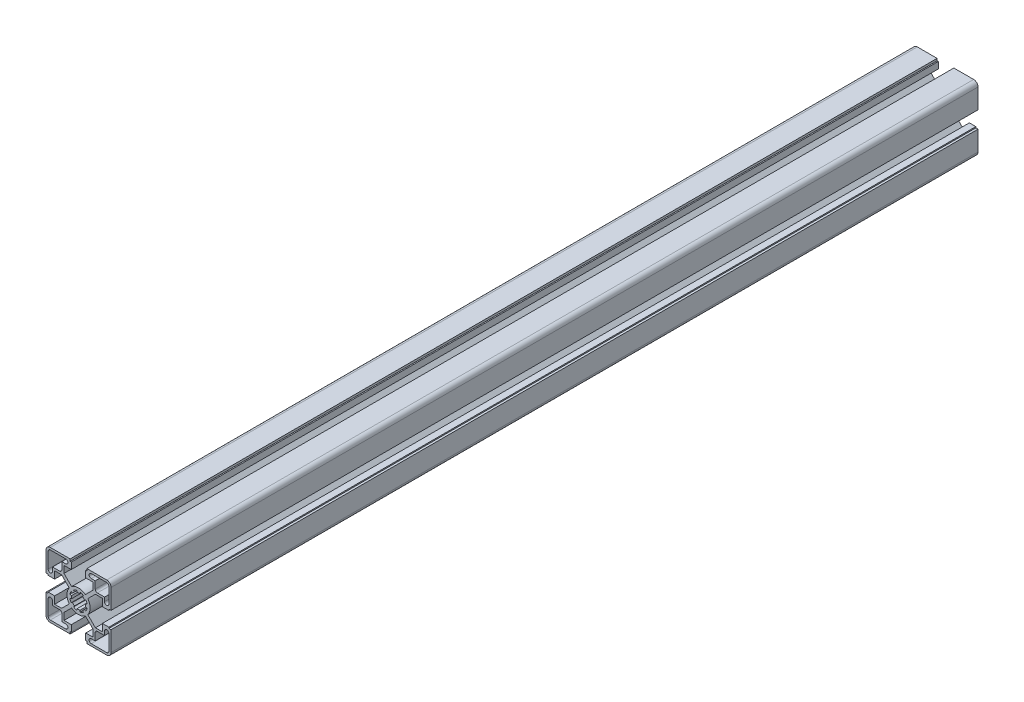
SolidWorks part; units mm, degrees
ref_plane "Front Plane" through (0, 0, 0) normal (0, 0, 1) x (1, 0, 0)
ref_plane "Top Plane" through (0, 0, 0) normal (0, 1, 0) x (1, 0, 0)
ref_plane "Right Plane" through (0, 0, 0) normal (1, 0, 0) x (0, 0, -1)
sketch "Sketch1" plane through (0, 0, 0) normal (0, 0, 1) x (1, 0, 0)
  line L2 (-19.5072, 22.5044) -> (-5.7912, 22.5044)
  line L3 (-5.7912, 22.5044) -> (-5.7912, 21.0058)
  line L4 (-5.7912, 21.0058) -> (-5.0038, 21.0058)
  line L6 (-5.0038, 21.0058) -> (-5.0038, 16.51)
  line L7 (-5.0038, 16.51) -> (-10.0457, 16.51)
  line L8 (-10.0457, 16.51) -> (-10.0457, 11.6801)
  line L9 (-10.0457, 11.6801) -> (-4.781, 6.4154)
  line L11 (-11.6801, 10.0457) -> (-6.4154, 4.781)
  line L12 (-16.51, 10.0457) -> (-11.6801, 10.0457)
  line L13 (-16.51, 5.0038) -> (-16.51, 10.0457)
  line L14 (-21.0058, 5.0038) -> (-16.51, 5.0038)
  line L15 (-21.0058, 5.7912) -> (-21.0058, 5.0038)
  line L16 (-22.5044, 5.7912) -> (-21.0058, 5.7912)
  line L17 (-22.5044, 19.5072) -> (-22.5044, 5.7912)
  line L18 (-18.0086, 11.5443) -> (-13.0429, 11.5443)
  line L19 (-18.0086, 11.5443) -> (-18.0086, 8.7884)
  line L20 (-11.5443, 18.0086) -> (-11.5443, 13.0429)
  line L21 (-21.0058, 19.5072) -> (-21.0058, 8.7884)
  line L23 (-11.5443, 18.0086) -> (-8.7884, 18.0086)
  line L24 (-19.5072, 21.0058) -> (-8.7884, 21.0058)
  line L25 (1.1893, 5.9789) -> (0.9762, 4.9077)
  line L26 (-1.1893, 5.9789) -> (-0.9762, 4.9077)
  line L27 (5.0686, 3.3868) -> (4.1605, 2.78)
  line L28 (3.3868, 5.0686) -> (2.78, 4.1605)
  line L29 (5.9789, -1.1893) -> (4.9077, -0.9762)
  line L30 (5.9789, 1.1893) -> (4.9077, 0.9762)
  line L31 (3.3868, -5.0686) -> (2.78, -4.1605)
  line L32 (5.0686, -3.3868) -> (4.1605, -2.78)
  line L33 (-1.1893, -5.9789) -> (-0.9762, -4.9077)
  line L34 (1.1893, -5.9789) -> (0.9762, -4.9077)
  line L35 (-5.0686, -3.3868) -> (-4.1605, -2.78)
  line L36 (-3.3868, -5.0686) -> (-2.78, -4.1605)
  line L37 (-5.9789, 1.1893) -> (-4.9077, 0.9762)
  line L38 (-5.9789, -1.1893) -> (-4.9077, -0.9762)
  line L39 (-3.3868, 5.0686) -> (-2.78, 4.1605)
  line L40 (-5.0686, 3.3868) -> (-4.1605, 2.78)
  line L41 (11.5443, 18.0086) -> (8.7884, 18.0086)
  line L42 (19.5072, 21.0058) -> (8.7884, 21.0058)
  line L43 (19.5072, 22.5044) -> (5.7912, 22.5044)
  line L44 (5.7912, 22.5044) -> (5.7912, 21.0058)
  line L45 (5.7912, 21.0058) -> (5.0038, 21.0058)
  line L46 (5.0038, 21.0058) -> (5.0038, 16.51)
  line L47 (5.0038, 16.51) -> (10.0457, 16.51)
  line L48 (10.0457, 16.51) -> (10.0457, 11.6801)
  line L49 (10.0457, 11.6801) -> (4.781, 6.4154)
  line L50 (11.6801, 10.0457) -> (6.4154, 4.781)
  line L51 (21.0058, 19.5072) -> (21.0058, 8.7884)
  line L52 (11.5443, 18.0086) -> (11.5443, 13.0429)
  line L53 (18.0086, 11.5443) -> (18.0086, 8.7884)
  line L54 (18.0086, 11.5443) -> (13.0429, 11.5443)
  line L55 (22.5044, 19.5072) -> (22.5044, 5.7912)
  line L56 (22.5044, 5.7912) -> (21.0058, 5.7912)
  line L57 (21.0058, 5.7912) -> (21.0058, 5.0038)
  line L58 (21.0058, 5.0038) -> (16.51, 5.0038)
  line L59 (16.51, 5.0038) -> (16.51, 10.0457)
  line L60 (16.51, 10.0457) -> (11.6801, 10.0457)
  line L61 (16.51, -10.0457) -> (11.6801, -10.0457)
  line L62 (16.51, -5.0038) -> (16.51, -10.0457)
  line L63 (21.0058, -5.0038) -> (16.51, -5.0038)
  line L64 (21.0058, -5.7912) -> (21.0058, -5.0038)
  line L65 (22.5044, -5.7912) -> (21.0058, -5.7912)
  line L66 (22.5044, -19.5072) -> (22.5044, -5.7912)
  line L67 (18.0086, -11.5443) -> (13.0429, -11.5443)
  line L68 (18.0086, -11.5443) -> (18.0086, -8.7884)
  line L69 (11.5443, -18.0086) -> (11.5443, -13.0429)
  line L70 (21.0058, -19.5072) -> (21.0058, -8.7884)
  line L71 (11.6801, -10.0457) -> (6.4154, -4.781)
  line L72 (10.0457, -11.6801) -> (4.781, -6.4154)
  line L73 (10.0457, -16.51) -> (10.0457, -11.6801)
  line L74 (5.0038, -16.51) -> (10.0457, -16.51)
  line L75 (5.0038, -21.0058) -> (5.0038, -16.51)
  line L76 (5.7912, -21.0058) -> (5.0038, -21.0058)
  line L77 (5.7912, -22.5044) -> (5.7912, -21.0058)
  line L78 (19.5072, -22.5044) -> (5.7912, -22.5044)
  line L79 (19.5072, -21.0058) -> (8.7884, -21.0058)
  line L80 (11.5443, -18.0086) -> (8.7884, -18.0086)
  line L81 (-11.5443, -18.0086) -> (-8.7884, -18.0086)
  line L82 (-19.5072, -21.0058) -> (-8.7884, -21.0058)
  line L83 (-19.5072, -22.5044) -> (-5.7912, -22.5044)
  line L84 (-5.7912, -22.5044) -> (-5.7912, -21.0058)
  line L85 (-5.7912, -21.0058) -> (-5.0038, -21.0058)
  line L86 (-5.0038, -21.0058) -> (-5.0038, -16.51)
  line L87 (-5.0038, -16.51) -> (-10.0457, -16.51)
  line L88 (-10.0457, -16.51) -> (-10.0457, -11.6801)
  line L89 (-10.0457, -11.6801) -> (-4.781, -6.4154)
  line L90 (-11.6801, -10.0457) -> (-6.4154, -4.781)
  line L91 (-21.0058, -19.5072) -> (-21.0058, -8.7884)
  line L92 (-11.5443, -18.0086) -> (-11.5443, -13.0429)
  line L93 (-18.0086, -11.5443) -> (-18.0086, -8.7884)
  line L94 (-18.0086, -11.5443) -> (-13.0429, -11.5443)
  line L95 (-22.5044, -19.5072) -> (-22.5044, -5.7912)
  line L96 (-22.5044, -5.7912) -> (-21.0058, -5.7912)
  line L97 (-21.0058, -5.7912) -> (-21.0058, -5.0038)
  line L98 (-21.0058, -5.0038) -> (-16.51, -5.0038)
  line L99 (-16.51, -5.0038) -> (-16.51, -10.0457)
  line L100 (-16.51, -10.0457) -> (-11.6801, -10.0457)
  arc A0 (-22.5044, 19.5072) -> (-19.5072, 22.5044) centre (-19.5072, 19.5072) cw
  arc A1 (-21.0058, 8.7884) -> (-18.0086, 8.7884) centre (-19.5072, 8.7884) ccw
  arc A2 (-21.0058, 19.5072) -> (-19.5072, 21.0058) centre (-19.5072, 19.5072) cw
  arc A3 (-8.7884, 21.0058) -> (-8.7884, 18.0086) centre (-8.7884, 19.5072) cw
  arc A4 (-11.5443, 13.0429) -> (-13.0429, 11.5443) centre (-13.0429, 13.0429) cw
  arc A5 (6.4154, -4.781) -> (6.4154, 4.781) centre (0, 0) ccw
  arc A6 (0.9762, 4.9077) -> (-0.9762, 4.9077) centre (0, 0) ccw
  arc A7 (-5.0686, 3.3868) -> (-5.9789, 1.1893) centre (0, 0) ccw
  arc A8 (4.1605, 2.78) -> (2.78, 4.1605) centre (0, 0) ccw
  arc A9 (4.9077, -0.9762) -> (4.9077, 0.9762) centre (0, 0) ccw
  arc A10 (2.78, -4.1605) -> (4.1605, -2.78) centre (0, 0) ccw
  arc A11 (-0.9762, -4.9077) -> (0.9762, -4.9077) centre (0, 0) ccw
  arc A12 (-4.1605, -2.78) -> (-2.78, -4.1605) centre (0, 0) ccw
  arc A13 (-4.9077, 0.9762) -> (-4.9077, -0.9762) centre (0, 0) ccw
  arc A14 (-2.78, 4.1605) -> (-4.1605, 2.78) centre (0, 0) ccw
  arc A15 (-5.9789, -1.1893) -> (-5.0686, -3.3868) centre (0, 0) ccw
  arc A16 (-3.3868, -5.0686) -> (-1.1893, -5.9789) centre (0, 0) ccw
  arc A17 (1.1893, -5.9789) -> (3.3868, -5.0686) centre (0, 0) ccw
  arc A18 (5.0686, -3.3868) -> (5.9789, -1.1893) centre (0, 0) ccw
  arc A19 (5.9789, 1.1893) -> (5.0686, 3.3868) centre (0, 0) ccw
  arc A20 (3.3868, 5.0686) -> (1.1893, 5.9789) centre (0, 0) ccw
  arc A21 (-1.1893, 5.9789) -> (-3.3868, 5.0686) centre (0, 0) ccw
  arc A22 (8.7884, 21.0058) -> (8.7884, 18.0086) centre (8.7884, 19.5072) ccw
  arc A23 (21.0058, 19.5072) -> (19.5072, 21.0058) centre (19.5072, 19.5072) ccw
  arc A24 (22.5044, 19.5072) -> (19.5072, 22.5044) centre (19.5072, 19.5072) ccw
  arc A25 (11.5443, 13.0429) -> (13.0429, 11.5443) centre (13.0429, 13.0429) ccw
  arc A26 (21.0058, 8.7884) -> (18.0086, 8.7884) centre (19.5072, 8.7884) cw
  arc A27 (21.0058, -8.7884) -> (18.0086, -8.7884) centre (19.5072, -8.7884) ccw
  arc A28 (11.5443, -13.0429) -> (13.0429, -11.5443) centre (13.0429, -13.0429) cw
  arc A29 (22.5044, -19.5072) -> (19.5072, -22.5044) centre (19.5072, -19.5072) cw
  arc A30 (21.0058, -19.5072) -> (19.5072, -21.0058) centre (19.5072, -19.5072) cw
  arc A31 (8.7884, -21.0058) -> (8.7884, -18.0086) centre (8.7884, -19.5072) cw
  arc A32 (-8.7884, -21.0058) -> (-8.7884, -18.0086) centre (-8.7884, -19.5072) ccw
  arc A33 (-21.0058, -19.5072) -> (-19.5072, -21.0058) centre (-19.5072, -19.5072) ccw
  arc A34 (-22.5044, -19.5072) -> (-19.5072, -22.5044) centre (-19.5072, -19.5072) ccw
  arc A35 (-11.5443, -13.0429) -> (-13.0429, -11.5443) centre (-13.0429, -13.0429) ccw
  arc A36 (-21.0058, -8.7884) -> (-18.0086, -8.7884) centre (-19.5072, -8.7884) cw
  arc A37 (4.781, 6.4154) -> (-4.781, 6.4154) centre (0, 0) ccw
  arc A38 (-4.781, -6.4154) -> (4.781, -6.4154) centre (0, 0) ccw
  arc A39 (-6.4154, 4.781) -> (-6.4154, -4.781) centre (0, 0) ccw
extrude "Boss-Extrude1" add sketch "Sketch1" along normal mid plane 600
